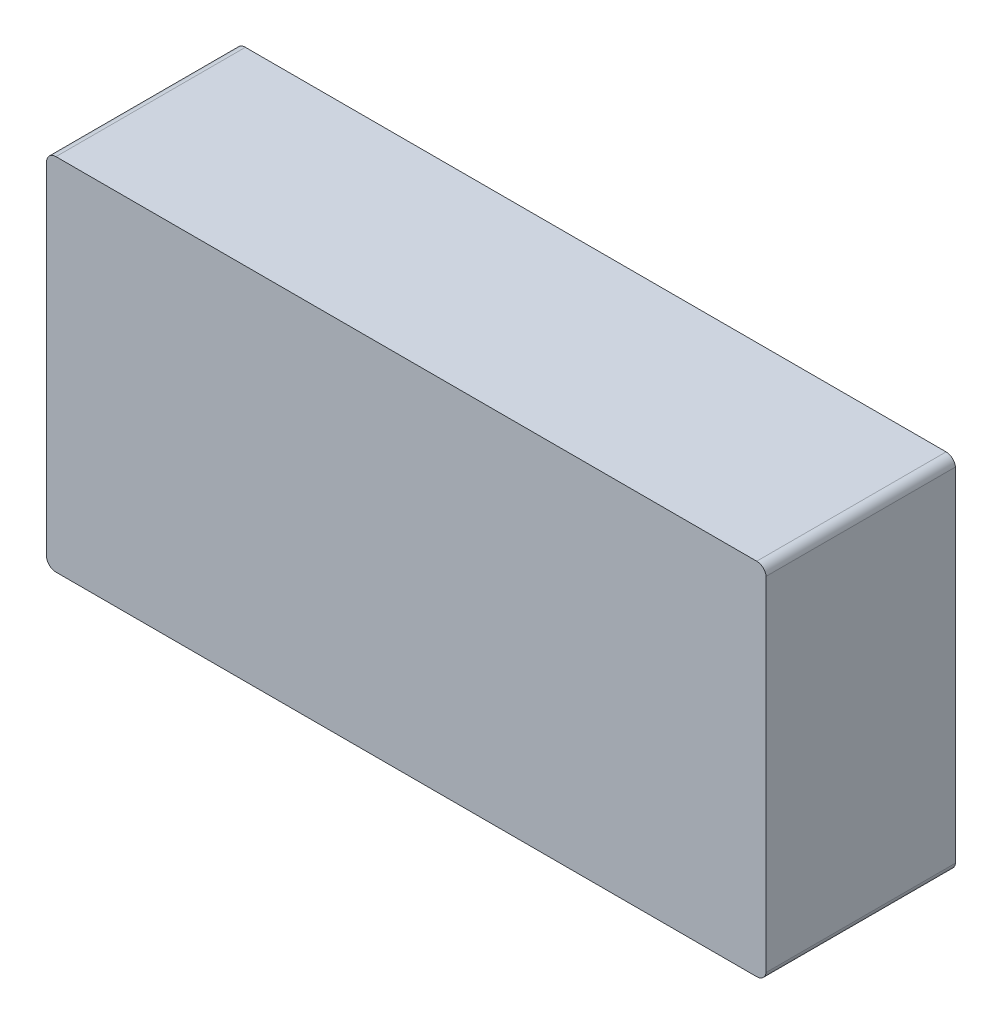
SolidWorks part; units mm, degrees
ref_plane "前视基准面" through (0, 0, 0) normal (0, 0, 1) x (1, 0, 0)
ref_plane "上视基准面" through (0, 0, 0) normal (0, 1, 0) x (1, 0, 0)
ref_plane "右视基准面" through (0, 0, 0) normal (1, 0, 0) x (0, 0, -1)
sketch "草图1" plane through (0, 0, 0) normal (0, 0, 1) x (1, 0, 0)
  line L1 (0, 0) -> (38, 0)
  line L2 (0, 0) -> (0, 19)
  line L3 (0, 19) -> (38, 19)
  line L4 (38, 0) -> (38, 19)
  dimension "D1" = 38
  dimension "D2" = 19
extrude "凸台-拉伸1" add sketch "草图1" along normal blind 10
sketch "草图2" plane through (38, 0, 0) normal (1, 0, 0) x (0, 0, -1)
  line L0 (0, 0) -> (0, 19) construction
  line L1 (-3.5, 14) -> (-2, 14)
  line L2 (-3.5, 14) -> (-3.5, 5)
  line L3 (-3.5, 5) -> (-2, 5)
  line L4 (-2, 14) -> (-2, 5)
  point P6 (0, 9.5)
  point P7 (-2, 9.5)
  dimension "D1" = 1.5
  dimension "D2" = 9
  dimension "D3" = 2
extrude "凸台-拉伸2" add sketch "草图2" along normal blind 9
sketch "草图3" plane through (0, 0, 2) normal (0, 0, -1) x (-1, 0, 0)
  line L0 (-47, 5) -> (-47, 14) construction
  line L1 (-47, 14) -> (-38, 14) construction
  circle A0 centre (-42.5, 9.5) radius 1.5
  point P5 (-47, 9.5)
  point P8 (-42.5, 14)
  dimension "D1" = 3
extrude "切除-拉伸1" cut sketch "草图3" against normal through all
ref_plane "基准面4" through (19, 0, 0) normal (1, 0, 0) x (0, 0, -1)
mirror "镜向3" about plane through (19, 0, 0) normal (1, 0, 0) of "切除-拉伸1", "凸台-拉伸2"
fillet "圆角2" radius 0.5 12 edges at (38, 0, 5) (38, 19, 5) (0, 19, 5) (0, 0, 5) (-9, 5, 2.75) (0, 5, 2.75) (-9, 14, 2.75) (0, 14, 2.75) (38, 5, 2.75) (47, 5, 2.75) (47, 14, 2.75) (38, 14, 2.75)
sketch "草图4" plane through (0, 0, 0) normal (0, 0, -1) x (-1, 0, 0)
  line L0 (-30, 9.5) -> (-8, 9.5) construction
  line L1 (-30, 13.5) -> (-8, 13.5)
  line L2 (-30, 5.5) -> (-8, 5.5)
  line L3 (-19, 5.5) -> (-19, -5.5) construction
  line L4 (-38, 4.5) -> (-38, 14.5) construction
  arc A0 (-30, 13.5) -> (-30, 5.5) centre (-30, 9.5) ccw
  arc A1 (-8, 5.5) -> (-8, 13.5) centre (-8, 9.5) ccw
  point P2 (-19, 9.5)
  point P7 (-19, 13.5)
  point P13 (-38, 9.5)
  dimension "D1" = 8
  dimension "D2" = 22
extrude "切除-拉伸2" cut sketch "草图4" against normal blind 1
sketch "草图5" plane through (0, 0, 0) normal (0, 0, -1) x (-1, 0, 0)
  line L1 (-37.9967, 0) -> (0, 0)
  line L2 (-37.9967, 0) -> (-37.9967, 19)
  line L3 (-37.9967, 19) -> (0, 19)
  line L4 (0, 0) -> (0, 19)
  line L5 (-48.8583, -3.0759) -> (10.7235, -3.0759)
  line L6 (-48.8583, -3.0759) -> (-48.8583, 21.2457)
  line L7 (-48.8583, 21.2457) -> (10.7235, 21.2457)
  line L8 (10.7235, -3.0759) -> (10.7235, 21.2457)
extrude "切除-拉伸3" cut sketch "草图5" against normal through all
